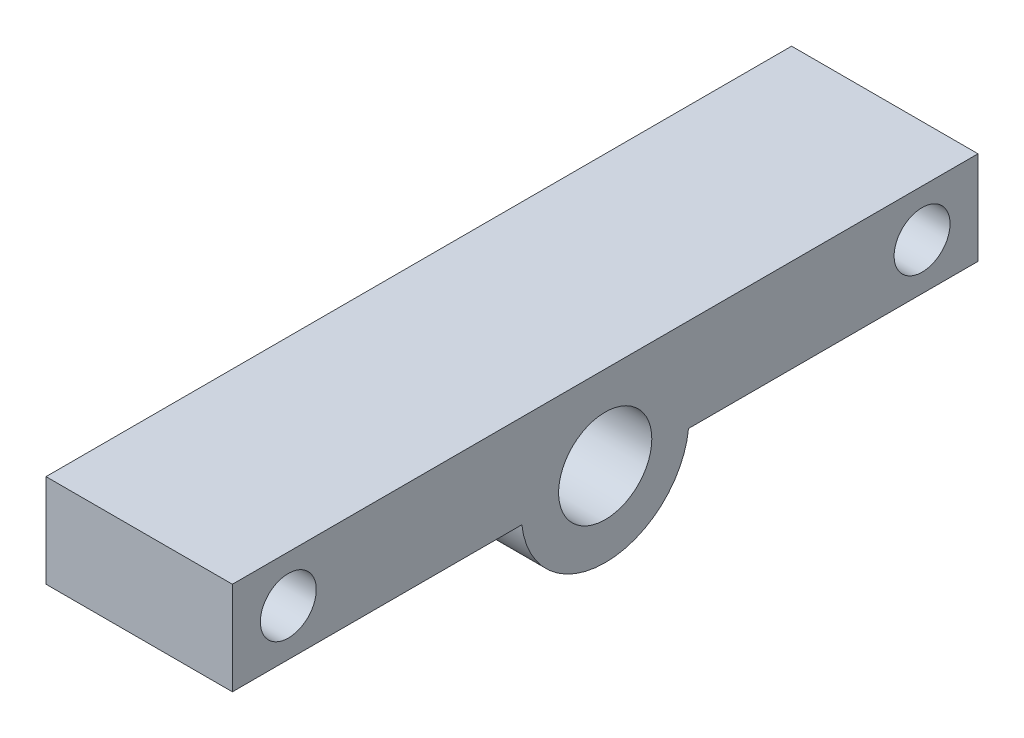
SolidWorks part; units mm, degrees
ref_plane "Płaszczyzna przednia" through (0, 0, 0) normal (0, 0, 1) x (1, 0, 0)
ref_plane "Płaszczyzna górna" through (0, 0, 0) normal (0, 1, 0) x (1, 0, 0)
ref_plane "Płaszczyzna prawa" through (0, 0, 0) normal (1, 0, 0) x (0, 0, -1)
sketch "Szkic1" plane through (0, 0, 0) normal (1, 0, 0) x (0, 0, -1)
  line L0 (-20, 4.5) -> (20, 4.5)
  line L1 (20, 4.5) -> (20, -0.5)
  line L2 (20, -0.5) -> (4.4721, -0.5)
  line L3 (0, 55) -> (0, -55) construction
  line L4 (-20, 4.5) -> (-20, -0.5)
  line L5 (-20, -0.5) -> (-4.4721, -0.5)
  line L6 (20, 2) -> (17, 2) construction
  circle A0 centre (0, 0) radius 2.5
  arc A1 (-4.4721, -0.5) -> (4.4721, -0.5) centre (0, 0) ccw
  arc A2 (0, 4.5) -> (-4.4721, -0.5) centre (0, 0) ccw construction
  arc A3 (4.4721, -0.5) -> (0, 4.5) centre (0, 0) ccw construction
  circle A4 centre (17, 2) radius 1.5
  circle A5 centre (-17, 2) radius 1.5
  point P7 (0, 4.5)
  dimension "D1" = 5
  dimension "D2" = 9
  dimension "D4" = 3
  dimension "D3" = 5
  dimension "D5" = 3
  dimension "D6" = 40
extrude "Dodanie-wyciągnięcie1" add sketch "Szkic1" along normal blind 10
